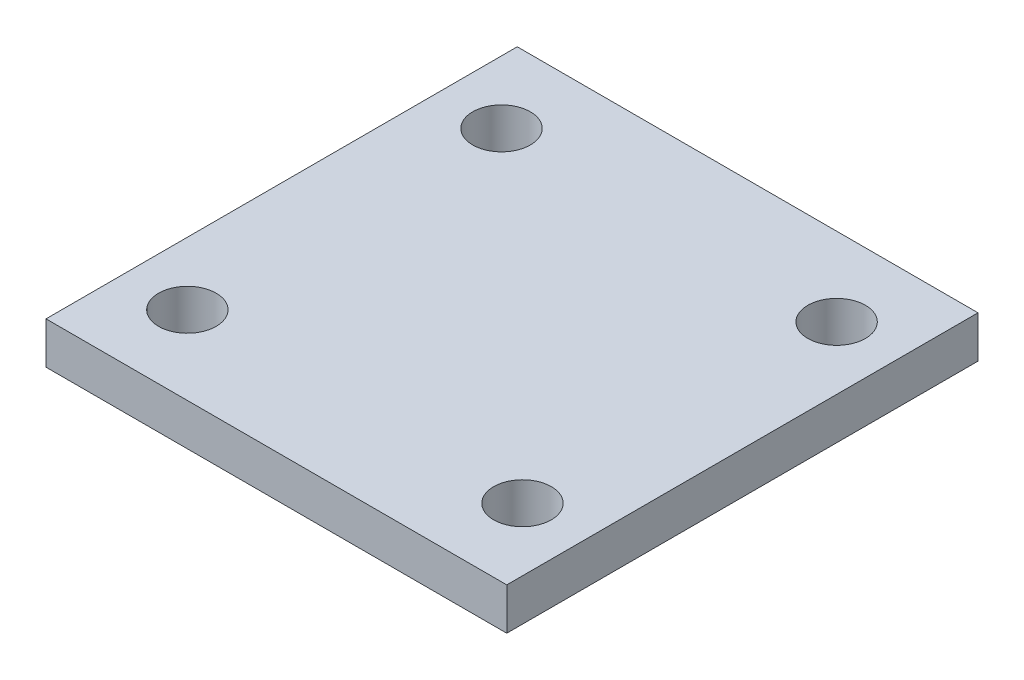
SolidWorks part; units mm, degrees
ref_plane "Front Plane" through (0, 0, 0) normal (0, 0, 1) x (1, 0, 0)
ref_plane "Top Plane" through (0, 0, 0) normal (0, 1, 0) x (1, 0, 0)
ref_plane "Right Plane" through (0, 0, 0) normal (1, 0, 0) x (0, 0, -1)
sketch "Sketch1" plane through (0, 0, 0) normal (0, 1, 0) x (1, 0, 0)
  line L1 (22, -22.5) -> (-22, -22.5)
  line L2 (22, -22.5) -> (22, 22.5)
  line L3 (22, 22.5) -> (-22, 22.5)
  line L4 (-22, -22.5) -> (-22, 22.5)
  line L5 (22, -22.5) -> (-22, 22.5) construction
  line L6 (22, 22.5) -> (-22, -22.5) construction
  point P0 (0, 0)
  point P6 (-16, -15)
  point P7 (-16, 15)
  point P8 (16, 15)
  point P9 (16, -15)
  dimension "D1" = 32
  dimension "D2" = 30
  dimension "D3" = 7.5
  dimension "D4" = 6
  dimension "D5" = 7.5
  dimension "D6" = 6
extrude "Boss-Extrude1" add sketch "Sketch1" along normal blind 4
hole_wizard "M5 Clearance Hole1" positions "Sketch3" profile "Sketch2" hole size "M5" standard "ISO" end condition through all
sketch "Sketch3" plane through (0, 4, 0) normal (0, 1, 0) x (1, 0, 0)
  line L0 (-22, -22.5) -> (22, 22.5) construction
  line L2 (22, -22.5) -> (-22, 22.5)
  point P0 (-16, -15)
  point P2 (-16, 15)
  point P4 (16, 15)
  point P6 (16, -15)
sketch "Sketch2" plane through (-16, 4, 15) normal (1, 0, 0) x (0, 0, 1)
  line L0 (0, 0) -> (0, 4)
  line L1 (0, 4) -> (2.75, 4)
  line L2 (2.75, 4) -> (2.75, 0)
  line L5 (2.75, 0) -> (0, 0)
  line L11 (0, -6.35) -> (0, 107.95) construction
  dimension "Thru Hole Dia." = 5.5
  dimension "Thru Hole Depth" = 4
